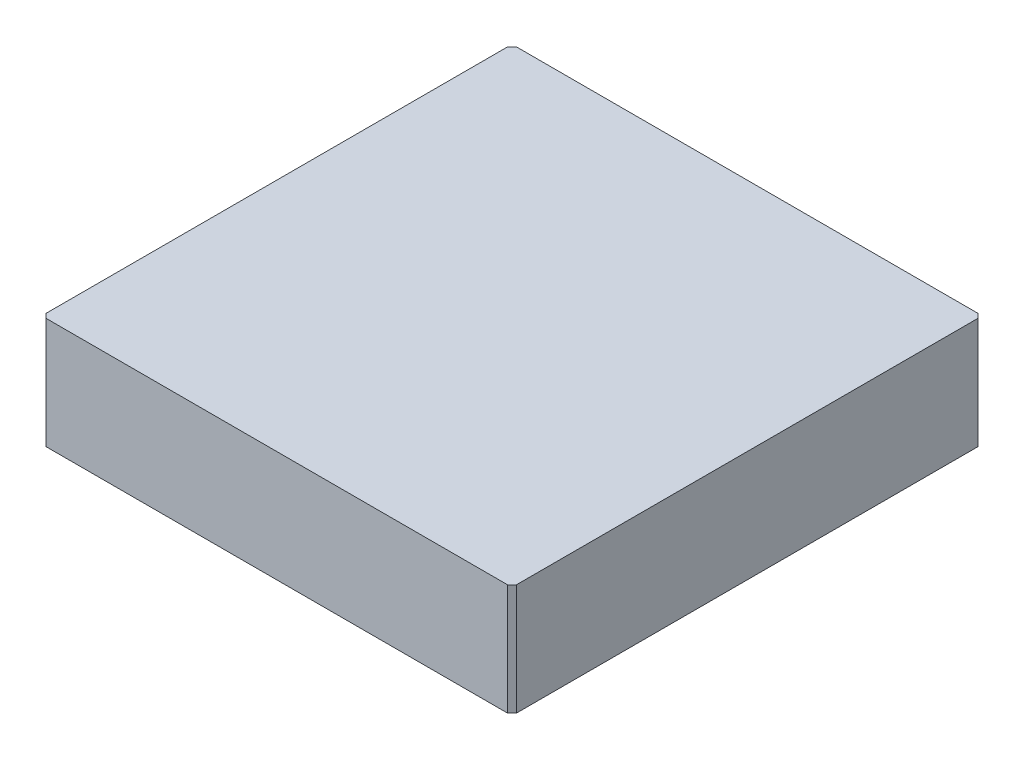
SolidWorks part; units mm, degrees
ref_plane "前视基准面" through (0, 0, 0) normal (0, 0, 1) x (1, 0, 0)
ref_plane "上视基准面" through (0, 0, 0) normal (0, 1, 0) x (1, 0, 0)
ref_plane "右视基准面" through (0, 0, 0) normal (1, 0, 0) x (0, 0, -1)
sketch "草图1" plane through (0, 0, 0) normal (0, 1, 0) x (1, 0, 0)
  line L1 (-55, 55) -> (55, 55)
  line L2 (-55, 55) -> (-55, -55)
  line L3 (-55, -55) -> (55, -55)
  line L4 (55, 55) -> (55, -55)
  line L5 (-55, 55) -> (55, -55) construction
  line L6 (-55, -55) -> (55, 55) construction
  point P0 (0, 0)
  dimension "D1" = 110
  dimension "D2" = 110
extrude "凸台-拉伸1" add sketch "草图1" along normal blind 26
chamfer "倒角1" distance 1 angle 45 4 edges at (-55, 13, -55) (55, 13, -55) (55, 13, 55) (-55, 13, 55)
